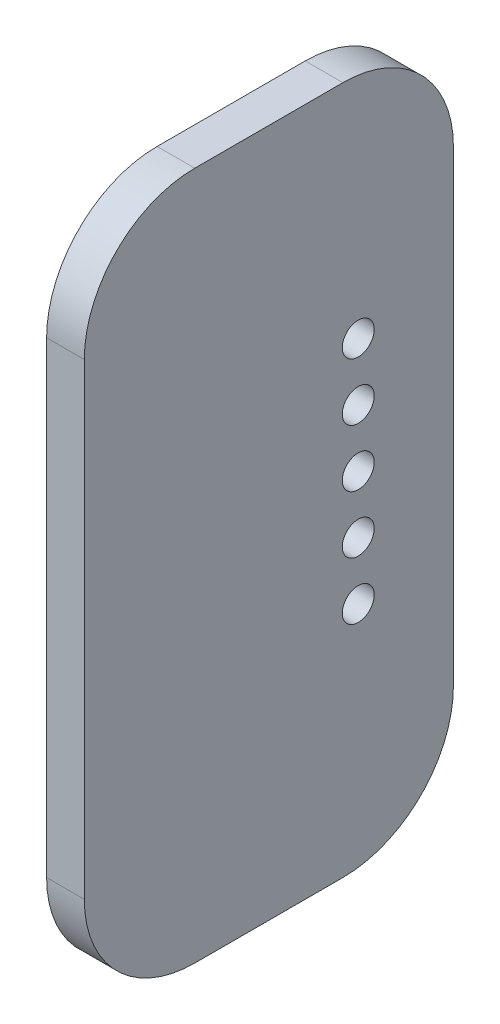
SolidWorks part; units mm, degrees
ref_plane "Front Plane" through (0, 0, 0) normal (0, 0, 1) x (1, 0, 0)
ref_plane "Top Plane" through (0, 0, 0) normal (0, 1, 0) x (1, 0, 0)
ref_plane "Right Plane" through (0, 0, 0) normal (1, 0, 0) x (0, 0, -1)
ref_plane "PX_p34_000" through (34, 0, 0) normal (1, 0, 0) x (0, 0, -1)
sketch "S_prism1" plane through (34, 0, 0) normal (1, 0, 0) x (0, 0, -1)
  line L0 (-17.55, -18.3) -> (-17.55, 18.3)
  line L1 (-26.2, 26.95) -> (-37.8, 26.95)
  line L2 (-46.45, 18.3) -> (-46.45, -18.3)
  line L3 (-37.8, -26.95) -> (-26.2, -26.95)
  arc A0 (-26.2, -26.95) -> (-17.55, -18.3) centre (-26.1999, -18.3001) ccw
  arc A1 (-17.55, 18.3) -> (-26.2, 26.95) centre (-26.1999, 18.3001) ccw
  arc A2 (-37.8, 26.95) -> (-46.45, 18.3) centre (-37.8001, 18.3001) ccw
  arc A3 (-46.45, -18.3) -> (-37.8, -26.95) centre (-37.8001, -18.3001) ccw
extrude "Boss_1" add sketch "S_prism1" along normal blind 2.95
ref_plane "PX_p33_900" through (33.9, 0, 0) normal (1, 0, 0) x (0, 0, -1)
sketch "S_hole2" plane through (33.9, 0, 0) normal (1, 0, 0) x (0, 0, -1)
  circle A0 centre (-25, -9) radius 1.25
  dimension "D1_S_hole2" = 2.5
  dimension "P2" = 25
  dimension "P3" = 9
extrude "Hole_2" cut sketch "S_hole2" along normal blind 3.2
sketch "S_hole3" plane through (33.9, 0, 0) normal (1, 0, 0) x (0, 0, -1)
  circle A0 centre (-25, -4.5) radius 1.25
  dimension "D1_S_hole3" = 2.5
  dimension "P2" = 25
  dimension "P3" = 4.5
extrude "Hole_3" cut sketch "S_hole3" along normal blind 3.2
sketch "S_hole4" plane through (33.9, 0, 0) normal (1, 0, 0) x (0, 0, -1)
  circle A0 centre (-25, 0) radius 1.25
  dimension "D1_S_hole4" = 2.5
  dimension "P2" = 25
extrude "Hole_4" cut sketch "S_hole4" along normal blind 3.2
sketch "S_hole5" plane through (33.9, 0, 0) normal (1, 0, 0) x (0, 0, -1)
  circle A0 centre (-25, 4.5) radius 1.25
  dimension "D1_S_hole5" = 2.5
  dimension "P2" = 25
  dimension "P3" = 4.5
extrude "Hole_5" cut sketch "S_hole5" along normal blind 3.2
sketch "S_hole6" plane through (33.9, 0, 0) normal (1, 0, 0) x (0, 0, -1)
  circle A0 centre (-25, 9) radius 1.25
  dimension "D1_S_hole6" = 2.5
  dimension "P2" = 25
  dimension "P3" = 9
extrude "Hole_6" cut sketch "S_hole6" along normal blind 3.2
equation "\"plate_t\" = 3"
equation "\"clearance\" = 0.5"
